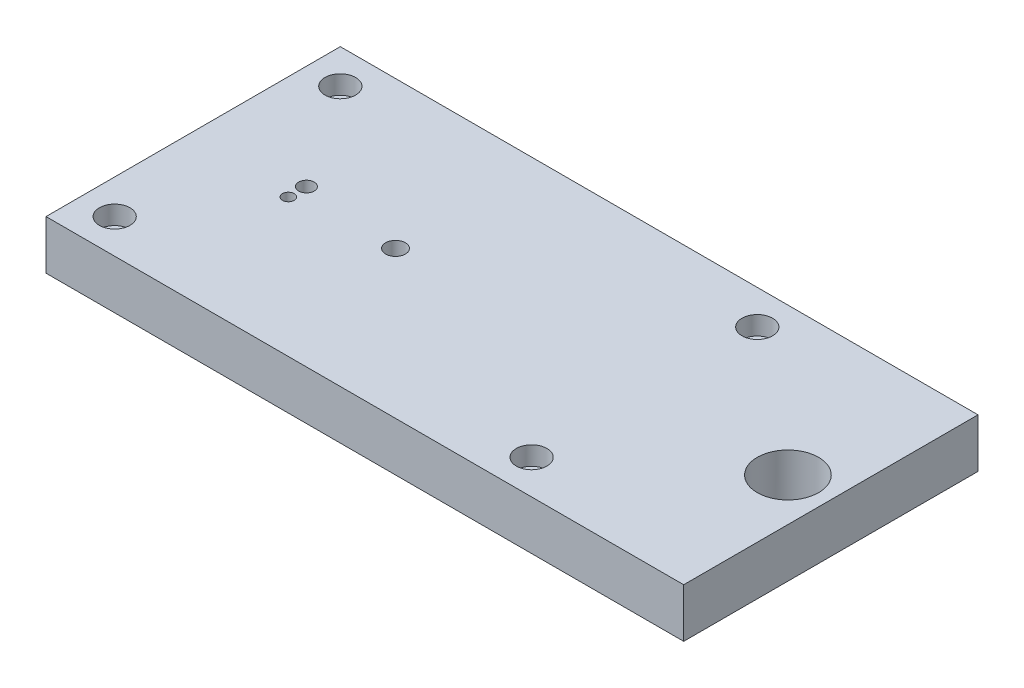
SolidWorks part; units mm, degrees
ref_plane "Front Plane" through (0, 0, 0) normal (0, 0, 1) x (1, 0, 0)
ref_plane "Top Plane" through (0, 0, 0) normal (0, 1, 0) x (1, 0, 0)
ref_plane "Right Plane" through (0, 0, 0) normal (1, 0, 0) x (0, 0, -1)
sketch "Sketch1" plane through (0, 0, 0) normal (0, 1, 0) x (1, 0, 0)
  line L1 (-65.2436, -52.8381) -> (99.8564, -52.8381)
  line L2 (-65.2436, -52.8381) -> (-65.2436, 23.3619)
  line L3 (-65.2436, 23.3619) -> (99.8564, 23.3619)
  line L4 (99.8564, -52.8381) -> (99.8564, 23.3619)
  dimension "D1" = 165.1
  dimension "D2" = 76.2
extrude "Boss-Extrude1" add sketch "Sketch1" along normal blind 12.7
sketch "Sketch2" plane through (0, 12.7, 0) normal (0, 1, 0) x (1, 0, 0)
  line L0 (99.8564, -52.8381) -> (99.8564, 23.3619) construction
  line L2 (99.8564, 23.3619) -> (-65.2436, 23.3619) construction
  line L3 (-65.2436, -52.8381) -> (99.8564, -52.8381) construction
  line L5 (-65.2436, 23.3619) -> (-65.2436, -52.8381) construction
  circle A0 centre (51.5964, -43.9481) radius 2.5527
  circle A1 centre (51.5964, 14.4719) radius 2.5527
  circle A2 centre (-56.3536, -43.9481) radius 2.5527
  circle A3 centre (-56.3536, 14.4719) radius 2.5527
  circle A4 centre (-56.3536, -43.9481) radius 3.9624
  circle A5 centre (-56.3536, 14.4719) radius 3.9624
  circle A6 centre (51.5964, 14.4719) radius 3.9624
  circle A7 centre (51.5964, -43.9481) radius 3.9624
  dimension "D1" = 5.1054
  dimension "D2" = 5.1054
  dimension "D3" = 5.1054
  dimension "D4" = 5.1054
  dimension "D13" = 7.9248
  dimension "D14" = 7.9248
  dimension "D15" = 7.9248
  dimension "D16" = 7.9248
  dimension "D5" = 48.26
  dimension "D6" = 8.89
  dimension "D7" = 48.26
  dimension "D8" = 8.89
  dimension "D9" = 8.89
  dimension "D10" = 8.89
  dimension "D11" = 8.89
  dimension "D12" = 8.89
extrude "Cut-Extrude3" cut sketch "Sketch2" against normal blind 4.826
sketch "Sketch10" plane through (0, 12.7, 0) normal (0, 1, 0) x (1, 0, 0)
  circle A0 centre (-56.3536, -43.9481) radius 2.5527 construction
  circle A1 centre (-56.3536, 14.4719) radius 2.5527 construction
  circle A2 centre (51.5964, 14.4719) radius 2.5527 construction
  circle A3 centre (51.5964, -43.9481) radius 2.5527 construction
  circle A4 centre (-56.3536, -43.9481) radius 2.5527
  circle A5 centre (-56.3536, 14.4719) radius 2.5527
  circle A6 centre (51.5964, 14.4719) radius 2.5527
  circle A7 centre (51.5964, -43.9481) radius 2.5527
extrude "Cut-Extrude9" cut sketch "Sketch10" against normal blind 22.352
sketch "Sketch11" plane through (0, 12.7, 0) normal (0, 1, 0) x (1, 0, 0)
  line L0 (99.8564, -52.8381) -> (99.8564, 23.3619) construction
  line L1 (-65.2436, -52.8381) -> (99.8564, -52.8381) construction
  line L2 (-65.2436, 23.3619) -> (-65.2436, -52.8381) construction
  line L3 (-12.8561, -14.7381) -> (-38.2561, -14.7381) construction
  circle A0 centre (88.7439, -14.7381) radius 7.9375
  circle A1 centre (-12.8561, -14.7381) radius 2.5527
  circle A2 centre (-38.2561, -12.4013) radius 2.0193
  circle A3 centre (-38.2561, -17.0749) radius 1.524
  dimension "D1" = 15.875
  dimension "D3" = 5.1054
  dimension "D7" = 4.0386
  dimension "D8" = 3.048
  dimension "D2" = 38.1
  dimension "D4" = 38.1
  dimension "D5" = 52.3875
  dimension "D6" = 101.6
  dimension "D9" = 4.6736
  dimension "D10" = 2.3368
  dimension "D11" = 25.4
  dimension "D12" = 11.1125
extrude "Cut-Extrude10" cut sketch "Sketch11" against normal blind 22.352
